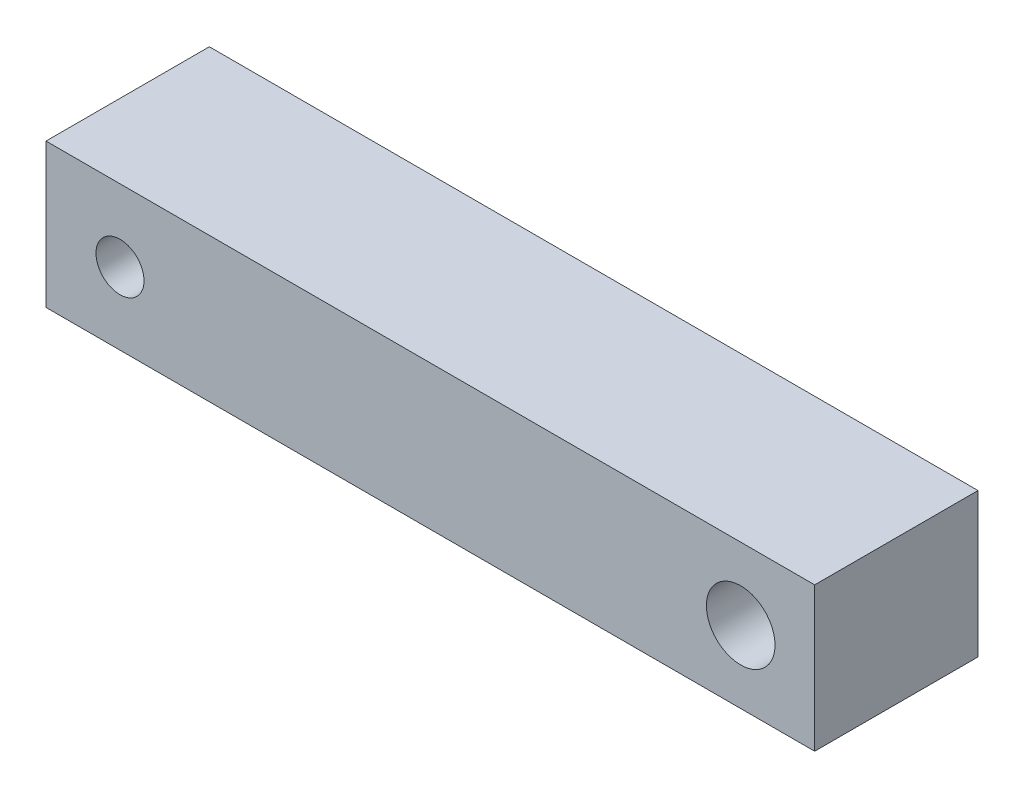
SolidWorks part; units mm, degrees
ref_plane "Front Plane" through (0, 0, 0) normal (0, 0, 1) x (1, 0, 0)
ref_plane "Top Plane" through (0, 0, 0) normal (0, 1, 0) x (1, 0, 0)
ref_plane "Right Plane" through (0, 0, 0) normal (1, 0, 0) x (0, 0, -1)
sketch "Sketch1" plane through (0, 0, 0) normal (0, 0, 1) x (1, 0, 0)
  line L0 (-32.3, 33.2309) -> (32.3, 33.2309) construction
  line L2 (40, 40.7309) -> (-40, 40.7309)
  line L3 (40, 40.7309) -> (40, 25.7309)
  line L4 (40, 25.7309) -> (-40, 25.7309)
  line L5 (-40, 40.7309) -> (-40, 25.7309)
  line L6 (40, 40.7309) -> (-40, 25.7309) construction
  line L7 (40, 25.7309) -> (-40, 40.7309) construction
  circle A0 centre (32.3, 33.2309) radius 3.57 construction
  circle A1 centre (32.3, 33.2309) radius 3.57
  circle A2 centre (-32.3, 33.2309) radius 2.5 construction
  circle A3 centre (-32.3, 33.2309) radius 2.5
  point P8 (0, 33.2309)
  dimension "D1" = 15
  dimension "D2" = 80
extrude "Boss-Extrude1" add sketch "Sketch1" along normal blind 17 from offset 10
